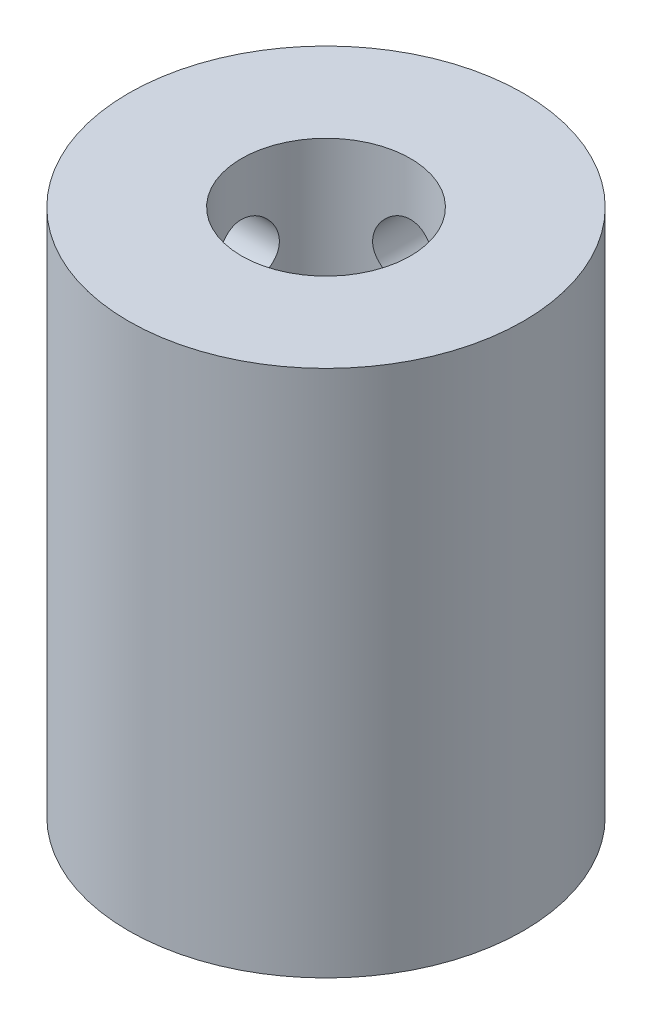
SolidWorks part; units mm, degrees
material "1060 Alloy"
ref_plane "Front Plane" through (0, 0, 0) normal (0, 0, 1) x (1, 0, 0)
ref_plane "Top Plane" through (0, 0, 0) normal (0, 1, 0) x (1, 0, 0)
ref_plane "Right Plane" through (0, 0, 0) normal (1, 0, 0) x (0, 0, -1)
sketch "Sketch1" plane through (0, 0, 0) normal (0, 1, 0) x (1, 0, 0)
  circle A0 centre (0, 0) radius 9.35
  circle A1 centre (0, 0) radius 2.5
extrude "Boss-Extrude1" add sketch "Sketch1" along normal blind 25
sketch "Sketch2" plane through (0, 25, 0) normal (0, 1, 0) x (1, 0, 0)
  circle A0 centre (0, 0) radius 4
extrude "Cut-Extrude1" cut sketch "Sketch2" against normal blind 12.5 contours A0
ref_plane "Plane1" through (-9.35, 0, 0) normal (-1, 0, 0) x (0, 0, 1)
sketch "Sketch3" plane through (-9.35, 0, 0) normal (-1, 0, 0) x (0, 0, 1)
  line L0 (9.35, 25) -> (-9.35, 25) construction
  line L1 (-9.35, 0) -> (9.35, 0) construction
  circle A0 centre (0, 21) radius 1.5
  circle A1 centre (0, 4) radius 1.5
  dimension "D1" = 3
  dimension "D2" = 3
  dimension "D3" = 4
  dimension "D4" = 4
extrude "Cut-Extrude2" cut sketch "Sketch3" against normal blind 8
pattern_circular "CirPattern1" count 2 every 90 about axis through (0, 12.5, 0) along (0, 1, 0) of "Cut-Extrude2"
